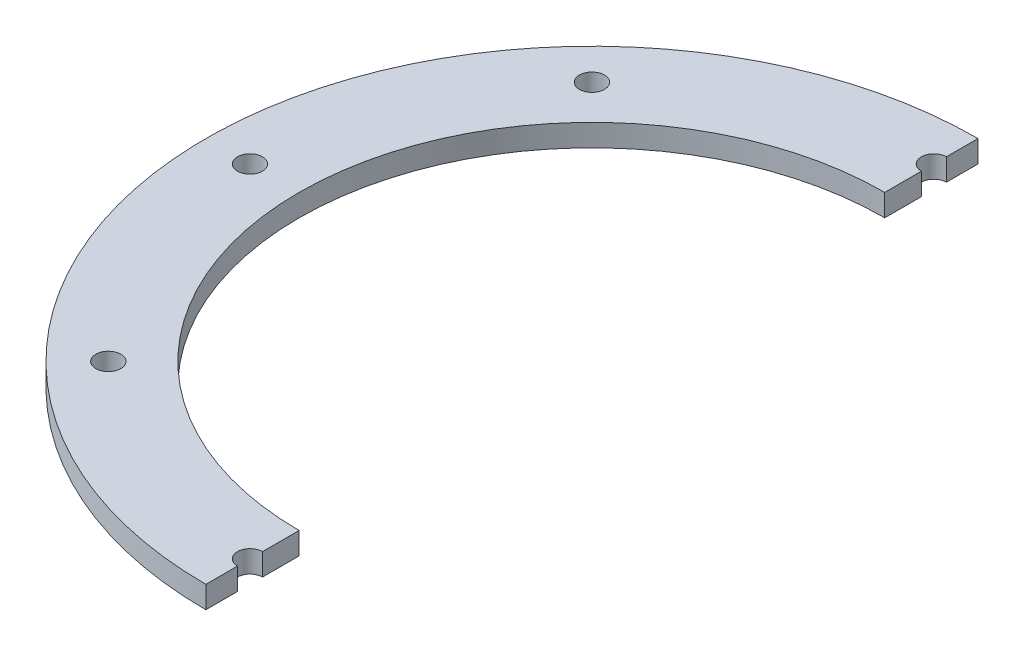
SolidWorks part; units mm, degrees
ref_plane "Front Plane" through (0, 0, 0) normal (0, 0, 1) x (1, 0, 0)
ref_plane "Top Plane" through (0, 0, 0) normal (0, 1, 0) x (1, 0, 0)
ref_plane "Right Plane" through (0, 0, 0) normal (1, 0, 0) x (0, 0, -1)
sketch "Sketch1" plane through (0, 0, 0) normal (0, -1, 0) x (1, 0, 0)
  line L0 (0, 52.5) -> (0, 48.2)
  line L1 (0, 44.8) -> (0, 39.8164)
  line L2 (0, -48.2) -> (0, -52.5)
  line L3 (0, -39.8164) -> (0, -44.8)
  line L4 (0, 0) -> (-46.5, 0) construction
  line L5 (0, 0) -> (-32.8805, 32.8805) construction
  arc A0 (0, 48.2) -> (0, 44.8) centre (0, 46.5) ccw
  arc A1 (0, 52.5) -> (0, -52.5) centre (0, 0) ccw
  arc A4 (0, -44.8) -> (0, -48.2) centre (0, -46.5) ccw
  circle A5 centre (-46.5, 0) radius 1.7
  circle A6 centre (46.5, 0) radius 1.7 [skipped]
  circle A7 centre (-32.8805, 32.8805) radius 1.7
  circle A8 centre (-32.8805, -32.8805) radius 1.7
  arc A9 (0, 39.8164) -> (0, -39.8164) centre (0, 0) ccw
  point P16 (0, 0)
  dimension "D1" = 3.4
  dimension "D3" = 105
  dimension "D6" = 45
  dimension "D4" = 4
  dimension "D5" = 2
extrude "Boss-Extrude1" add sketch "Sketch1" along normal blind 3
